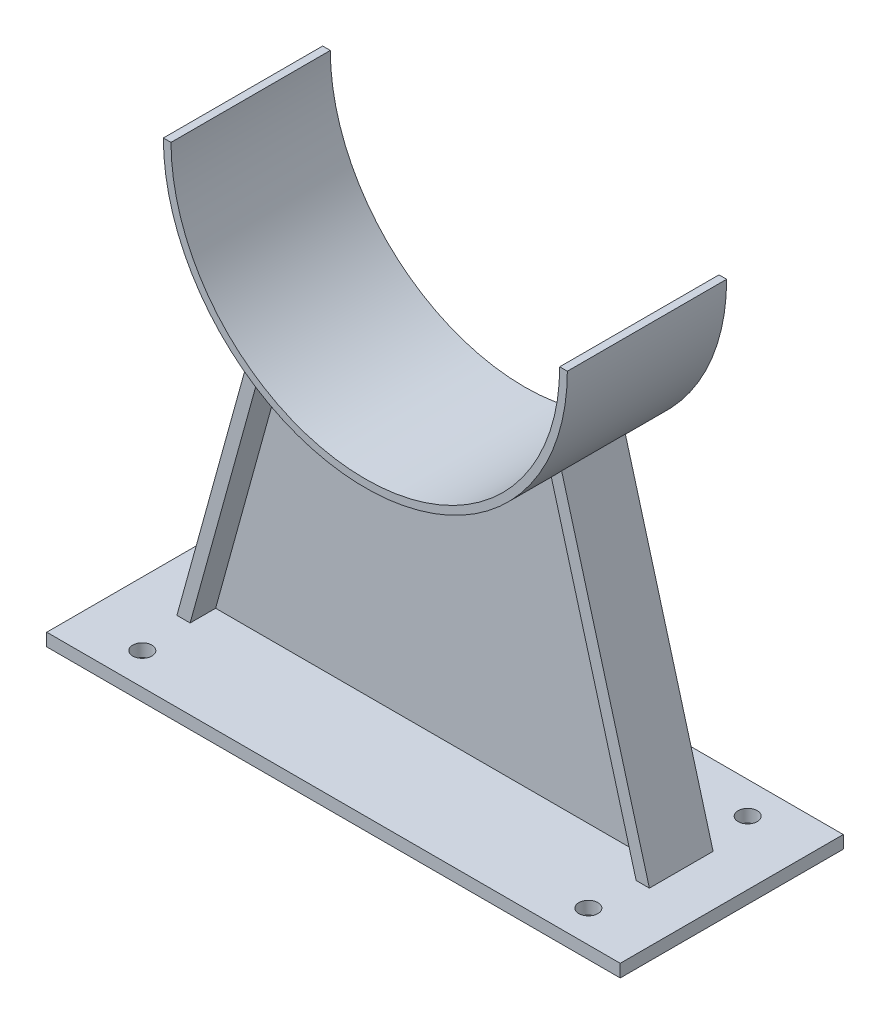
SolidWorks part; units mm, degrees
ref_plane "Front Plane" through (0, 0, 0) normal (0, 0, 1) x (1, 0, 0)
ref_plane "Top Plane" through (0, 0, 0) normal (0, 1, 0) x (1, 0, 0)
ref_plane "Right Plane" through (0, 0, 0) normal (1, 0, 0) x (0, 0, -1)
sketch "Sketch1" plane through (0, 0, 0) normal (0, 0, 1) x (1, 0, 0)
  line L0 (-317, 0) -> (-305, 0)
  line L1 (317, 0) -> (305, 0)
  arc A0 (-317, 0) -> (317, 0) centre (0, 0) ccw
  arc A1 (-305, 0) -> (305, 0) centre (0, 0) ccw
  dimension "D1" = 305
  dimension "D2" = 12
extrude "Boss-Extrude1" add sketch "Sketch1" along normal mid plane 250 contours A0 L1 A1 L0
sketch "Sketch2" plane through (0, 0, 0) normal (0, 0, 1) x (1, 0, 0)
  line L0 (-216.8211, -231.2523) -> (-350, -713.1894)
  line L1 (-216.8211, -231.2523) -> (0, 0) construction
  line L2 (0, 0) -> (0, -1261.981) construction
  line L3 (216.8211, -231.2523) -> (350, -713.1894)
  line L4 (-350, -713.1894) -> (350, -713.1894)
  arc A0 (-317, 0) -> (317, 0) centre (0, 0) ccw construction
  arc A1 (-216.8211, -231.2523) -> (216.8211, -231.2523) centre (0, 0) ccw
  dimension "D1" = 500
  dimension "D3" = 350
extrude "Boss-Extrude2" add sketch "Sketch2" along normal mid plane 20
sketch "Sketch3" plane through (0, -713.1894, 0) normal (0, -1, 0) x (1, 0, 0)
  line L0 (317, 125) -> (-317, 125) construction
  line L1 (-450, 175) -> (450, 175)
  line L2 (-450, 175) -> (-450, -175)
  line L3 (-450, -175) -> (450, -175)
  line L4 (450, 175) -> (450, -175)
  line L5 (-317, -125) -> (317, -125) construction
  line L6 (350, 10) -> (350, -10) construction
  circle A0 centre (-350, 125) radius 15
  circle A1 centre (350, 125) radius 15
  circle A2 centre (-350, -125) radius 15
  circle A3 centre (350, -125) radius 15
  dimension "D5" = 30
  dimension "D6" = 50
  dimension "D8" = 100
  dimension "D9" = 50
  dimension "D1" = 50
  dimension "D2" = 50
  dimension "D3" = 100
  dimension "D4" = 100
  dimension "D7" = 100
extrude "Boss-Extrude3" add sketch "Sketch3" along normal blind 20
sketch "Sketch5" plane through (-142.0677, 39.2591, 0) normal (-0.9639, 0.2664, 0) x (0, 0, 1)
  line L0 (10, -280.6501) -> (-10, -280.6501) construction
  line L1 (-50, -260.6501) -> (50, -260.6501)
  line L2 (-50, -260.6501) -> (-50, -800.6501)
  line L3 (-50, -800.6501) -> (50, -800.6501)
  line L4 (50, -260.6501) -> (50, -800.6501)
  line L5 (-10, -280.6501) -> (-10, -780.6501) construction
  line L6 (10, -317) -> (10, -165.1461) construction
  line L7 (10, -780.6501) -> (-10, -780.6501) construction
  dimension "D1" = 20
  dimension "D2" = 40
  dimension "D3" = 40
  dimension "D4" = 20
extrude "Boss-Extrude4" add sketch "Sketch5" along normal blind 20
mirror "Mirror1" about plane through (0, 0, 0) normal (1, 0, 0) of "Boss-Extrude4"
sketch "Sketch6" plane through (0, 0, -125) normal (0, 0, -1) x (-1, 0, 0)
  line L0 (-305, 0) -> (305, 0)
  arc A0 (-305, 0) -> (305, 0) centre (0, 0) ccw construction
  arc A1 (-305, 0) -> (305, 0) centre (0, 0) ccw
extrude "Cut-Extrude1" cut sketch "Sketch6" against normal blind 676
